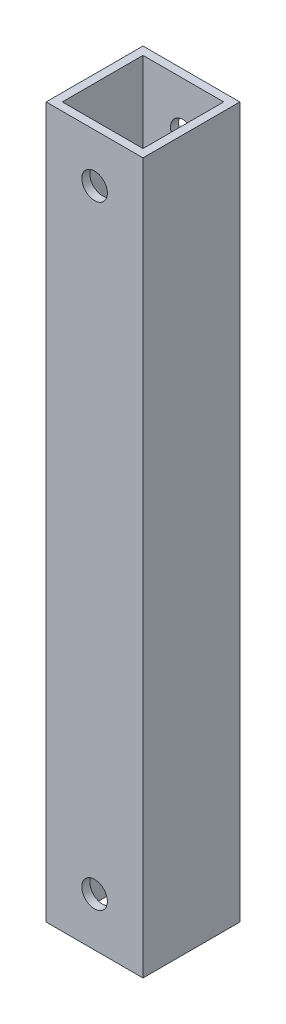
SolidWorks part; units mm, degrees
material "Plain Carbon Steel"
ref_plane "Front Plane" through (0, 0, 0) normal (0, 0, 1) x (1, 0, 0)
ref_plane "Top Plane" through (0, 0, 0) normal (0, 1, 0) x (1, 0, 0)
ref_plane "Right Plane" through (0, 0, 0) normal (1, 0, 0) x (0, 0, -1)
sketch "Sketch1" plane through (0, 0, 0) normal (0, 1, 0) x (1, 0, 0)
  line L0 (0, 19.05) -> (3.175, 19.05) construction
  line L1 (0, 0) -> (38.1, 0)
  line L2 (0, 0) -> (0, 38.1)
  line L3 (0, 38.1) -> (38.1, 38.1)
  line L4 (38.1, 0) -> (38.1, 38.1)
  line L5 (3.175, 3.175) -> (34.925, 3.175)
  line L6 (3.175, 3.175) -> (3.175, 34.925)
  line L7 (3.175, 34.925) -> (34.925, 34.925)
  line L8 (34.925, 3.175) -> (34.925, 34.925)
  line L9 (34.925, 19.05) -> (38.1, 19.05) construction
  line L10 (19.05, 3.175) -> (19.05, 0) construction
  line L11 (19.05, 34.925) -> (19.05, 38.1) construction
  dimension "D1" = 38.1
  dimension "D2" = 38.1
  dimension "D3" = 3.175
extrude "Boss-Extrude1" add sketch "Sketch1" along normal blind 279.4
hole_wizard "X (0.397) Diameter Hole1" positions "Sketch3" profile "Sketch2" hole size "X" standard "ANSI Inch" end condition through all
sketch "Sketch3" plane through (0, 0, 0) normal (0, 0, 1) x (1, 0, 0)
  line L0 (19.05, 0) -> (19.05, 19.05) construction
  line L1 (0, 0) -> (38.1, 0) construction
  line L2 (19.05, 19.05) -> (19.05, 260.35) construction
  line L3 (19.05, 260.35) -> (19.05, 279.4) construction
  line L4 (0, 279.4) -> (38.1, 279.4) construction
  point P0 (19.05, 260.35)
  point P2 (19.05, 19.05)
  dimension "D1" = 19.05
sketch "Sketch2" plane through (19.05, 260.35, 0) normal (1, 0, 0) x (0, -1, 0)
  line L0 (0, 0) -> (0, 38.1)
  line L1 (0, 38.1) -> (5.0419, 38.1)
  line L2 (5.0419, 38.1) -> (5.0419, 0)
  line L5 (5.0419, 0) -> (0, 0)
  line L11 (0, -6.35) -> (0, 107.95) construction
  dimension "Thru Hole Dia." = 10.0838
  dimension "Thru Hole Depth" = 38.1
